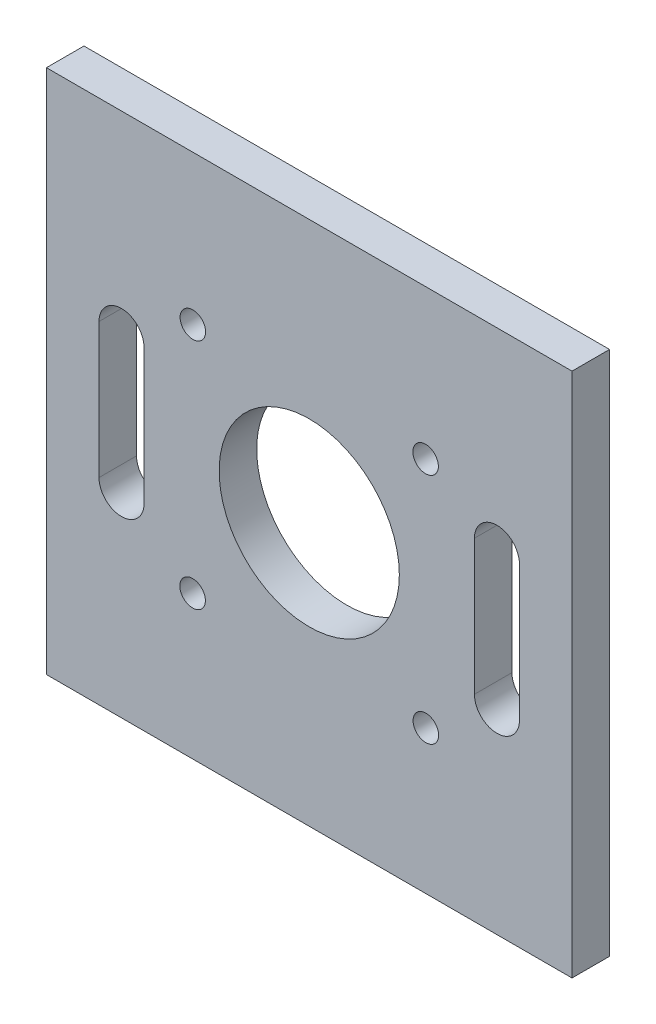
SolidWorks part; units mm, degrees
ref_plane "Front Plane" through (0, 0, 0) normal (0, 0, 1) x (1, 0, 0)
ref_plane "Top Plane" through (0, 0, 0) normal (0, 1, 0) x (1, 0, 0)
ref_plane "Right Plane" through (0, 0, 0) normal (1, 0, 0) x (0, 0, -1)
sketch "Sketch1" plane through (0, 0, 0) normal (0, 0, 1) x (1, 0, 0)
  line L1 (35, 35) -> (-35, 35)
  line L2 (35, 35) -> (35, -35)
  line L3 (35, -35) -> (-35, -35)
  line L4 (-35, 35) -> (-35, -35)
  line L5 (35, 35) -> (-35, -35) construction
  line L6 (35, -35) -> (-35, 35) construction
  point P0 (0, 0)
  dimension "D1" = 70
  dimension "D2" = 70
extrude "Boss-Extrude1" add sketch "Sketch1" along normal blind 5
sketch "Sketch2" plane through (0, 0, 5) normal (0, 0, 1) x (1, 0, 0)
  line L0 (0, 31.0352) -> (0, -30.2256) construction
  circle A0 centre (0, 0) radius 12
  circle A1 centre (15.5, 15.1128) radius 1.7
  circle A2 centre (15.5323, -15.8872) radius 1.7
  circle A3 centre (-15.5323, -15.8872) radius 1.7
  circle A4 centre (-15.5, 15.1128) radius 1.7
  dimension "D1" = 24
  dimension "D2" = 3.4
  dimension "D3" = 3.4
  dimension "D4" = 31
  dimension "D5" = 31
extrude "Cut-Extrude6" cut sketch "Sketch2" against normal through all contours A1 | A2 | A0 | A3 | A4
sketch "Sketch3" plane through (0, 0, 5) normal (0, 0, 1) x (1, 0, 0)
  line L0 (-25, 9.2232) -> (-25, -8.7768) construction
  line L7 (-22, 9.2232) -> (-22, -8.7768)
  line L8 (-28, 9.2232) -> (-28, -8.7768)
  line L9 (0, 21.6022) -> (0, -20.4096) construction
  line L10 (25, 9.2232) -> (25, -8.7768) construction
  line L11 (22, 9.2232) -> (22, -8.7768)
  line L12 (28, 9.2232) -> (28, -8.7768)
  arc A2 (-22, 9.2232) -> (-28, 9.2232) centre (-25, 9.2232) ccw
  arc A3 (-28, -8.7768) -> (-22, -8.7768) centre (-25, -8.7768) ccw
  arc A4 (22, 9.2232) -> (28, 9.2232) centre (25, 9.2232) cw
  arc A5 (28, -8.7768) -> (22, -8.7768) centre (25, -8.7768) cw
  point P2 (-25, 0.2232)
  point P13 (25, 0.2232)
  dimension "D1" = 6
  dimension "D2" = 18
  dimension "D3" = 25
extrude "Cut-Extrude7" cut sketch "Sketch3" against normal through all contours L8 A3 L7 A2 | L11 A5 L12 A4
